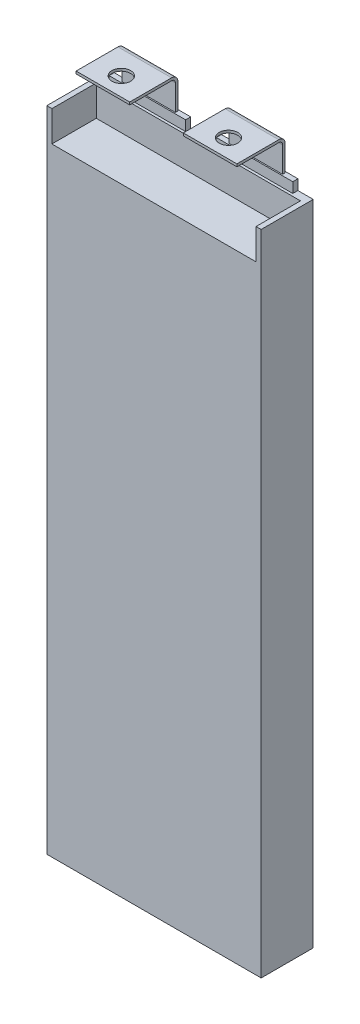
SolidWorks part; units mm, degrees
ref_plane "Front Plane" through (0, 0, 0) normal (0, 0, 1) x (1, 0, 0)
ref_plane "Top Plane" through (0, 0, 0) normal (0, 1, 0) x (1, 0, 0)
ref_plane "Right Plane" through (0, 0, 0) normal (1, 0, 0) x (0, 0, -1)
sketch "Sketch1" plane through (0, 0, 0) normal (0, 0, 1) x (1, 0, 0)
  line L1 (-21, 0) -> (21, 0)
  line L2 (-21, 0) -> (-21, 127)
  line L3 (-21, 127) -> (21, 127)
  line L4 (21, 0) -> (21, 127)
  dimension "D1" = 127
  dimension "D2" = 42
extrude "Boss-Extrude1" add sketch "Sketch1" along normal mid plane 10.2
ref_plane "Tab Mid Plane" through (0, 0, -4.6) normal (0, 0, -1) x (-1, 0, 0)
sketch "Sketch2" plane through (0, 0, 5.1) normal (0, 0, 1) x (1, 0, 0)
  line L0 (21, 127) -> (-21, 127) construction
  line L1 (-20, 127) -> (20, 127)
  line L2 (-20, 127) -> (-20, 121)
  line L3 (-20, 121) -> (20, 121)
  line L4 (20, 127) -> (20, 121)
  line L5 (-21, 127) -> (-21, 0) construction
  point P8 (0, 127)
  dimension "D1" = 1
  dimension "D2" = 6
extrude "Cut-Extrude1" cut sketch "Sketch2" against normal offset from surface (8.7 mm away) 1 up to plane "Tab Mid Plane"
sketch "Sketch3" plane through (0, 0, -4.6) normal (0, 0, -1) x (-1, 0, 0)
  line L0 (-21, 127) -> (21, 127) construction
  line L1 (-18, 127) -> (-3, 127)
  line L2 (-18, 127) -> (-18, 129)
  line L3 (-18, 129) -> (-3, 129)
  line L4 (-3, 127) -> (-3, 129)
  line L5 (-3, 127) -> (3, 127) construction
  line L6 (3, 127) -> (18, 127)
  line L7 (3, 127) -> (3, 129)
  line L8 (3, 129) -> (18, 129)
  line L9 (18, 127) -> (18, 129)
  point P10 (-10.5, 129)
  point P11 (10.5, 129)
  point P12 (0, 127)
  dimension "D1" = 21
  dimension "D2" = 2
  dimension "D3" = 15
extrude "Boss-Extrude2" add sketch "Sketch3" along normal mid plane 1
sketch "Tab Profile" plane through (0, 129, 0) normal (0, 1, 0) x (1, 0, 0)
  line L0 (-18, 5.1) -> (-3, 4.1) construction
  line L1 (-15.75, 4.85) -> (-5.25, 4.85)
  line L2 (-15.75, 4.85) -> (-15.75, 4.35)
  line L3 (-15.75, 4.35) -> (-5.25, 4.35)
  line L4 (-5.25, 4.85) -> (-5.25, 4.35)
  line L5 (5.25, 4.85) -> (15.75, 4.85)
  line L6 (5.25, 4.85) -> (5.25, 4.35)
  line L7 (5.25, 4.35) -> (15.75, 4.35)
  line L8 (15.75, 4.85) -> (15.75, 4.35)
  line L9 (3, 5.1) -> (18, 4.1) construction
  line L10 (-15.75, 4.35) -> (-5.25, 4.85) construction
  line L11 (5.25, 4.35) -> (15.75, 4.85) construction
  point P16 (-10.5, 4.6)
  point P17 (10.5, 4.6)
  dimension "D1" = 10.5
  dimension "D2" = 0.5
sketch "Tab Bend" plane through (0, 0, 0) normal (1, 0, 0) x (0, 0, -1)
  line L0 (4.6, 129) -> (4.6, 135)
  line L1 (5.1, 129) -> (4.1, 129) construction
  line L2 (4.6, 135) -> (-4.6, 135)
  line L3 (4.6, 129) -> (-6.6, 129) construction
  point P1 (-1, 129)
  dimension "D2" = 11.2
  dimension "D1" = 6
  dimension "D3" = 3.6
sweep "Tabs" add profiles "Tab Profile" path "Tab Bend"
fillet "Fillet2" radius 0.75 1 edges at (10.5, 134.75, -4.35)
fillet "Fillet1" radius 1.25 1 edges at (10.5, 135.25, -4.85)
fillet "Fillet4" radius 0.75 1 edges at (-10.5, 134.75, -4.35)
fillet "Fillet3" radius 1.25 1 edges at (-10.5, 135.25, -4.85)
hole_wizard "#6 Clearance Hole1" positions "Sketch9" profile "Sketch10" hole size "#6" standard "ANSI Inch"
sketch "Sketch9" plane through (0, 135.25, 0) normal (0, 1, 0) x (1, 0, 0)
  line L0 (-15.75, 2.6) -> (-5.25, -4.6) construction
  line L4 (-15.75, 3.6) -> (-15.75, -4.6) construction
  point P0 (-10.5, -1)
  dimension "D1" = 7.2
sketch "Sketch10" plane through (-10.5, 135.25, 1) normal (1, 0, 0) x (0, 0, 1)
  line L0 (0, 0) -> (0, 0.5)
  line L1 (0, 0.5) -> (1.8288, 0.5)
  line L2 (1.8288, 0.5) -> (1.8288, 0)
  line L5 (1.8288, 0) -> (0, 0)
  line L11 (0, -6.35) -> (0, 107.95) construction
  dimension "Thru Hole Dia." = 3.6576
  dimension "Thru Hole Depth" = 0.5
hole_wizard "#6 Clearance Hole2" positions "Sketch11" profile "Sketch12" hole size "#6" standard "ANSI Inch"
sketch "Sketch11" plane through (0, 135.25, 0) normal (0, 1, 0) x (1, 0, 0)
  line L0 (5.25, 2.6) -> (15.75, -4.6) construction
  line L1 (5.25, 3.6) -> (5.25, -4.6) construction
  point P0 (10.5, -1)
  dimension "D1" = 7.2
sketch "Sketch12" plane through (10.5, 135.25, 1) normal (1, 0, 0) x (0, 0, 1)
  line L0 (0, 0) -> (0, 0.5)
  line L1 (0, 0.5) -> (1.8288, 0.5)
  line L2 (1.8288, 0.5) -> (1.8288, 0)
  line L5 (1.8288, 0) -> (0, 0)
  line L11 (0, -6.35) -> (0, 107.95) construction
  dimension "Thru Hole Dia." = 3.6576
  dimension "Thru Hole Depth" = 0.5
split "Split1" [suppressed] bodies to split 108
mirror "Mirror3" [suppressed] about plane through (0, 0, -4.6) normal (0, 0, -1)
delete or keep bodies "Body-Delete/Keep 1" [suppressed] type delete bodies bodies 110 109
